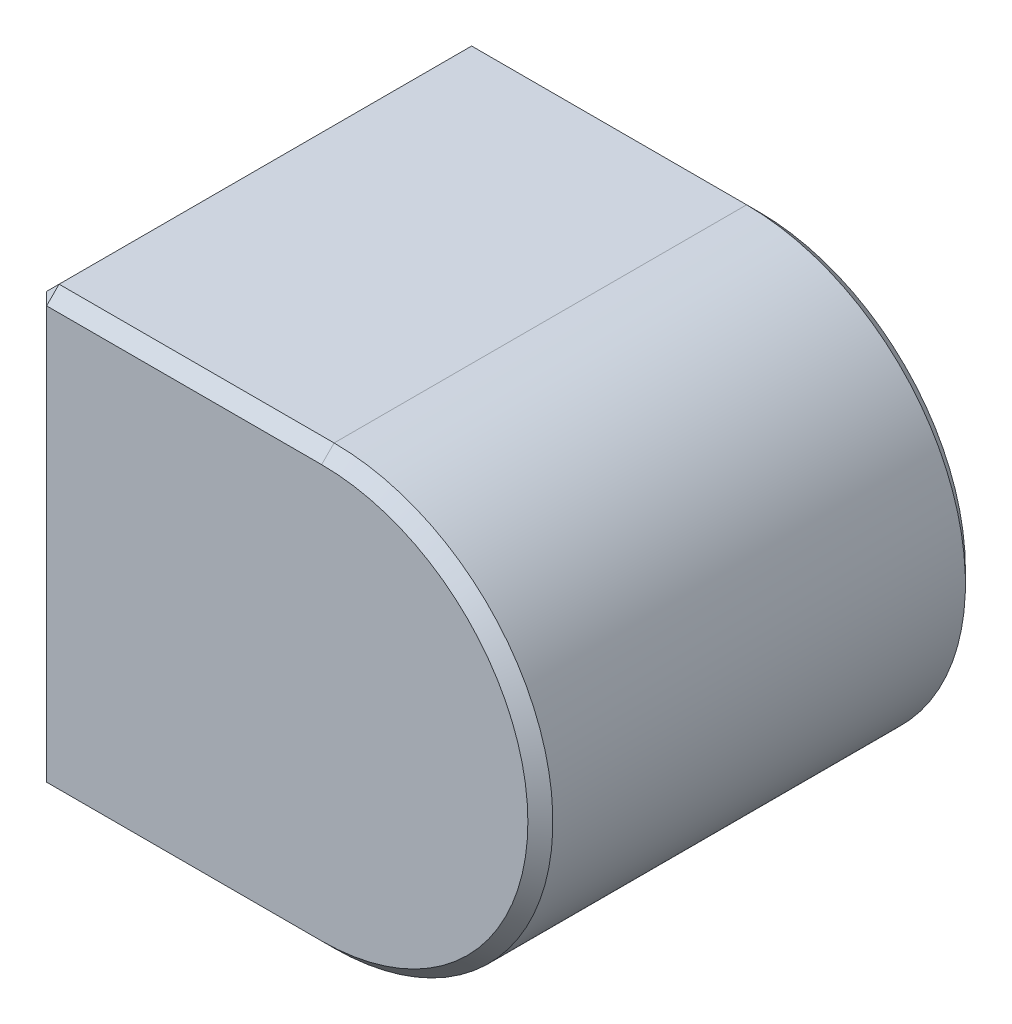
SolidWorks part; units mm, degrees
ref_plane "Front Plane" through (0, 0, 0) normal (0, 0, 1) x (1, 0, 0)
ref_plane "Top Plane" through (0, 0, 0) normal (0, 1, 0) x (1, 0, 0)
ref_plane "Right Plane" through (0, 0, 0) normal (1, 0, 0) x (0, 0, -1)
sketch "Sketch3" plane through (0, 0, 0) normal (0, 0, 1) x (1, 0, 0)
  line L0 (0, 35) -> (46, 35)
  line L1 (46, 35) -> (46, -35)
  line L2 (46, -35) -> (0, -35)
  arc A0 (0, 35) -> (0, -35) centre (0, 0) ccw
  dimension "D1" = 70
  dimension "D2" = 46
extrude "Boss-Extrude1" add sketch "Sketch3" along normal blind 70
sketch "Sketch4" plane through (46, 0, 0) normal (1, 0, 0) x (0, 0, -1)
  line L0 (0, 0) -> (-70, 0) construction
  line L1 (-70, -35) -> (-70, 35) construction
  circle A0 centre (-38, 0) radius 25
  dimension "D1" = 50
  dimension "D2" = 32
extrude "Boss-Extrude2" add sketch "Sketch4" along normal blind 5
sketch "Sketch5" plane through (0, 0, 0) normal (0, 0, -1) x (-1, 0, 0)
  circle A0 centre (0, 0) radius 26
  dimension "D1" = 52
chamfer "Chamfer1" distance 2 angle 45 10 edges at (23, -35, 0) (-35, 0, 0) (23, 35, 0) (46, -35, 35) (46, 0, 0) (46, 35, 35) (23, 35, 70) (46, 0, 70) (23, -35, 70) (-35, 0, 70)
extrude "Cut-Extrude1" cut sketch "Sketch5" against normal blind 5
chamfer "Chamfer3" distance 1 angle 45 4 edges at (-26, 0, 5) (51, 0, 13) (46, 0, 63) (-26, 0, 0)
mirror "Mirror1" about plane through (0, 0, 0) normal (1, 0, 0) of bodies 104
delete or keep bodies "Body-Delete/Keep 1" type delete bodies bodies 104
sketch "Sketch6" plane through (0, 0, 0) normal (0, 1, 0) x (1, 0, 0)
  line L0 (35, -35) -> (-51, -35) construction
  line L1 (35, -68) -> (35, -2) construction
  line L2 (-51, -14) -> (-51, -62) construction
  point P6 (-8, -35)
